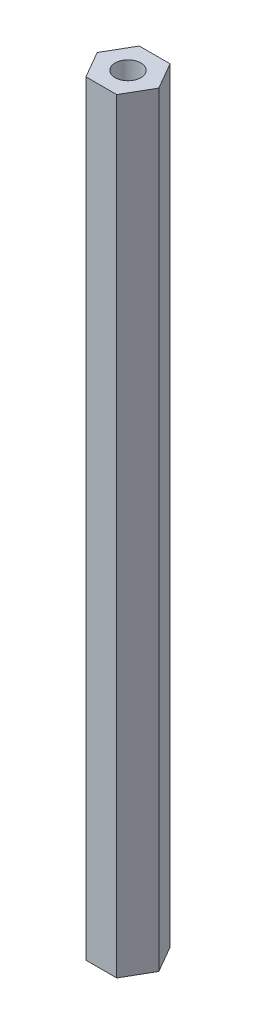
SolidWorks part; units mm, degrees
ref_plane "Front" through (0, 0, 0) normal (0, 0, 1) x (1, 0, 0)
ref_plane "Top" through (0, 0, 0) normal (0, 1, 0) x (1, 0, 0)
ref_plane "Right" through (0, 0, 0) normal (1, 0, 0) x (0, 0, -1)
sketch "Sketch1" plane through (0, 0, 0) normal (0, 1, 0) x (1, 0, 0)
  line L1 (1.5, 2.5981) -> (-1.5, 2.5981)
  line L2 (-1.5, 2.5981) -> (-3, 0)
  line L3 (-3, 0) -> (-1.5, -2.5981)
  line L4 (-1.5, -2.5981) -> (1.5, -2.5981)
  line L5 (1.5, -2.5981) -> (3, 0)
  line L6 (3, 0) -> (1.5, 2.5981)
  circle A0 centre (0, 0) radius 2.5981 construction
  dimension "D1" = 3
extrude "Boss-Extrude1" add sketch "Sketch1" along normal blind 74.5
sketch "Sketch2" plane through (0, 74.5, 0) normal (0, 1, 0) x (1, 0, 0)
  circle A0 centre (0, 0) radius 1.25
  dimension "D1" = 2.5
extrude "Cut-Extrude1" cut sketch "Sketch2" against normal through all
